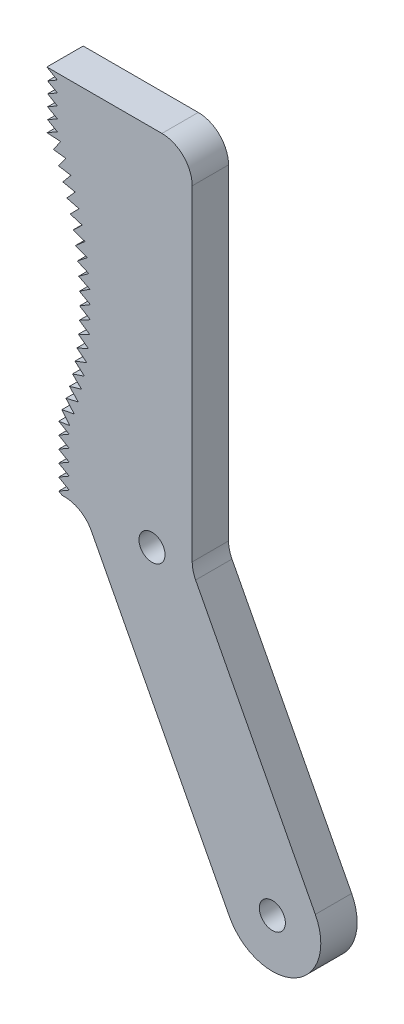
SolidWorks part; units mm, degrees
material "ABS"
ref_plane "Front Plane" through (0, 0, 0) normal (0, 0, 1) x (1, 0, 0)
ref_plane "Top Plane" through (0, 0, 0) normal (0, 1, 0) x (1, 0, 0)
ref_plane "Right Plane" through (0, 0, 0) normal (1, 0, 0) x (0, 0, -1)
sketch "Sketch1" plane through (0, 0, 0) normal (0, 0, 1) x (1, 0, 0)
  line L0 (0, 60) -> (0, 0)
  line L1 (0, 0) -> (20.3305, -39.0214)
  line L2 (6.1409, -46.4143) -> (-18.0414, 0)
  line L5 (-24, 50.7155) -> (-24, 60)
  line L6 (-24, 60) -> (0, 60)
  line L7 (-22.0414, 11.1985) -> (-22.0414, 0)
  line L8 (-22.0414, 0) -> (-18.0414, 0)
  arc A0 (20.3305, -39.0214) -> (6.1409, -46.4143) centre (13.2357, -42.7179) cw
  arc A2 (-24, 50.7155) -> (-22.0414, 11.1985) centre (-66.8069, 28.7868) cw
  circle A4 centre (-6.6369, 0) radius 2.15
  circle A5 centre (13.2357, -42.7179) radius 2.15
  dimension "D4" = 16
  dimension "D6" = 4.3
  dimension "D7" = 8
  dimension "D8" = 4.3
  dimension "D1" = 24
  dimension "D2" = 4
  dimension "D3" = 44
  dimension "D5" = 60
extrude "Boss-Extrude1" add sketch "Sketch1" along normal blind 6
sketch "Sketch2" plane through (0, 0, 6) normal (0, 0, 1) x (1, 0, 0)
  line L0 (-24, 60) -> (-22.2679, 59)
  line L1 (-22.2679, 59) -> (-24, 58)
  line L2 (-24, 50.7155) -> (-24, 60) construction
  line L3 (-24, 58) -> (-24, 60)
  dimension "D1" = 2
extrude "Cut-Extrude1" cut sketch "Sketch2" against normal through all
pattern_linear "LPattern1" count 5 spacing 1.85 along (0, -1, 0) of "Cut-Extrude1"
fillet "Fillet1" radius 5 3 edges at (0, 60, 3) (-18.0414, 0, 3) (0, 0, 3)
sketch "Sketch3" plane through (0, 0, 6) normal (0, 0, 1) x (1, 0, 0)
  line L0 (-23.9544, 50.6263) -> (-21.7414, 50.4593)
  line L1 (-21.7414, 50.4593) -> (-22.9926, 48.6263)
  line L5 (-23.9544, 50.6263) -> (-22.9926, 48.6263)
  arc A0 (-22.0414, 11.1985) -> (-23.9544, 50.6263) centre (-66.8069, 28.7868) ccw construction
  arc A1 (-22.0414, 11.1985) -> (-23.9544, 50.6263) centre (-66.8069, 28.7868) ccw construction
  dimension "D1" = 2
extrude "Cut-Extrude2" cut sketch "Sketch3" against normal through all
pattern_circular "CirPattern1" count 20 over 47 about axis through (-66.8069, 28.7868, 0) along (0, 0, 1) of "Cut-Extrude2"
sketch "Sketch4" plane through (0, 0, 6) normal (0, 0, 1) x (1, 0, 0)
  line L0 (-22.0414, 10.3307) -> (-20.3093, 9.3307)
  line L1 (-20.3093, 9.3307) -> (-22.0414, 8.3307)
  line L2 (-22.0414, 10.3307) -> (-22.0414, 0) construction
  line L3 (-22.0414, 8.3307) -> (-22.0414, 10.3307)
  dimension "D1" = 2
extrude "Cut-Extrude3" cut sketch "Sketch4" against normal through all
pattern_linear "LPattern2" count 8 spacing 2 along (0, -1, 0) of "Cut-Extrude3"
